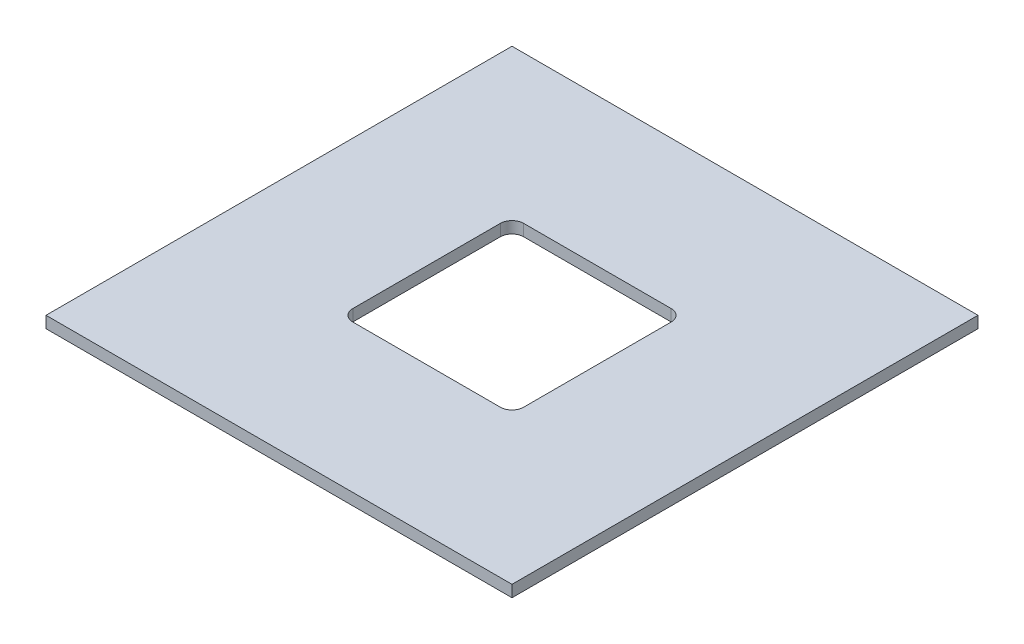
SolidWorks part; units mm, degrees
ref_plane "Front Plane" through (0, 0, 0) normal (0, 0, 1) x (1, 0, 0)
ref_plane "Top Plane" through (0, 0, 0) normal (0, 1, 0) x (1, 0, 0)
ref_plane "Right Plane" through (0, 0, 0) normal (1, 0, 0) x (0, 0, -1)
sketch "Sketch1" plane through (0, 0, 0) normal (0, 1, 0) x (1, 0, 0)
  line L1 (3, 0) -> (41, 0)
  line L2 (0, 3) -> (0, 41)
  line L3 (3, 44) -> (41, 44)
  line L4 (44, 3) -> (44, 41)
  line L5 (-38, -38) -> (82, -38)
  line L6 (-38, -38) -> (-38, 82)
  line L7 (-38, 82) -> (82, 82)
  line L8 (82, -38) -> (82, 82)
  arc A0 (3, 0) -> (0, 3) centre (3, 3) cw
  arc A1 (41, 0) -> (44, 3) centre (41, 3) ccw
  arc A2 (41, 44) -> (44, 41) centre (41, 41) cw
  arc A3 (0, 41) -> (3, 44) centre (3, 41) cw
  point P7 (0, 0)
  point P14 (0, 44)
  dimension "D2" = 3
  dimension "D1" = 44
  dimension "D3" = 120
  dimension "D4" = 38
  dimension "D5" = 38
extrude "Boss-Extrude1" add sketch "Sketch1" along normal blind 3 contours L2 A3 L3 A2 L4 A1 L1 A0
